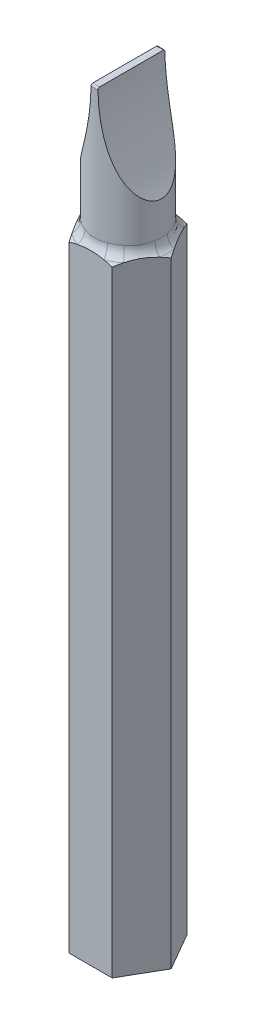
SolidWorks part; units mm, degrees
ref_plane "Front Plane" through (0, 0, 0) normal (0, 0, 1) x (1, 0, 0)
ref_plane "Top Plane" through (0, 0, 0) normal (0, 1, 0) x (1, 0, 0)
ref_plane "Right Plane" through (0, 0, 0) normal (1, 0, 0) x (0, 0, -1)
sketch "Sketch1" plane through (0, 0, 0) normal (0, 1, 0) x (1, 0, 0)
  line L1 (2.5, 0) -> (1.25, 2.1651)
  line L2 (1.25, 2.1651) -> (-1.25, 2.1651)
  line L3 (-1.25, 2.1651) -> (-2.5, 0)
  line L4 (-2.5, 0) -> (-1.25, -2.1651)
  line L5 (-1.25, -2.1651) -> (1.25, -2.1651)
  line L6 (1.25, -2.1651) -> (2.5, 0)
  circle A0 centre (0, 0) radius 2.1651 construction
  dimension "D1" = 2.5
extrude "Boss-Extrude1" add sketch "Sketch1" along normal blind 36
sketch "Sketch2" plane through (0, 0, 0) normal (0, 0, 1) x (1, 0, 0)
  line L0 (-2.5, 35.65) -> (-2.5, 36)
  line L1 (-2.5, 36) -> (-2.5, 0) construction
  line L2 (-2.5, 36) -> (-1.95, 36)
  line L3 (-2.5, 36) -> (-1.25, 36) construction
  line L4 (-1.95, 36) -> (-2.5, 35.65)
  line L5 (0, 36) -> (0, 0) construction
  line L6 (-1.25, 36) -> (1.25, 36) construction
  line L7 (-1.25, 0) -> (1.25, 0) construction
  dimension "D1" = 0.35
  dimension "D2" = 0.55
revolve "Cut-Revolve1" cut sketch "Sketch2" angle 360 about L5
sketch "Sketch3" plane through (0, 36, 0) normal (0, 1, 0) x (1, 0, 0)
  circle A1 centre (0, 0) radius 1.95
  circle A2 centre (0, 0) radius 1.95
  dimension "D1" = 0
extrude "Boss-Extrude2" add sketch "Sketch3" along normal blind 8
fillet "Fillet1" radius 0.75 1 edges at (0, 36, 1.95)
sketch "Sketch4" plane through (0, 0, 0) normal (0, 0, 1) x (1, 0, 0)
  line L0 (0, 44) -> (0, 36.3888) construction
  line L1 (1.95, 44) -> (-1.95, 44) construction
  line L2 (0, 44) -> (-0.2, 44)
  line L3 (-1.95, 44) -> (-1.95, 36.4117) construction
  line L4 (-0.2, 44) -> (-0.2, 46.9101) construction
  line L5 (-1.95, 38.3487) -> (-1.95, 44.3487)
  line L6 (-1.95, 44.3487) -> (0, 44.3487)
  line L7 (0, 44.3487) -> (0, 44)
  arc A0 (-0.2, 44) -> (-1.95, 38.3487) centre (-10.2, 44) cw
  spline S0 degree 3 poles (-0.6521, 36.4117) (-0.4419, 36.4117) (-0.2212, 36.3889) (0.1093, 36.3888) (0.221, 36.3937) (0.4396, 36.4054) (0.5468, 36.4117) (0.6521, 36.4117) knots 0 0 0 0 0.5 0.5 0.75 0.75 1 1 1 1 construction
  dimension "D1" = 0.2
  dimension "D3" = 10
  dimension "D2" = 6
extrude "Cut-Extrude1" cut sketch "Sketch4" against normal mid plane 8
mirror "Mirror1" about plane through (0, 0, 0) normal (1, 0, 0) of "Cut-Extrude1"
fillet "Fillet2" radius 0.1 2 edges at (0, 44, -1.95) (0, 44, 1.95)
